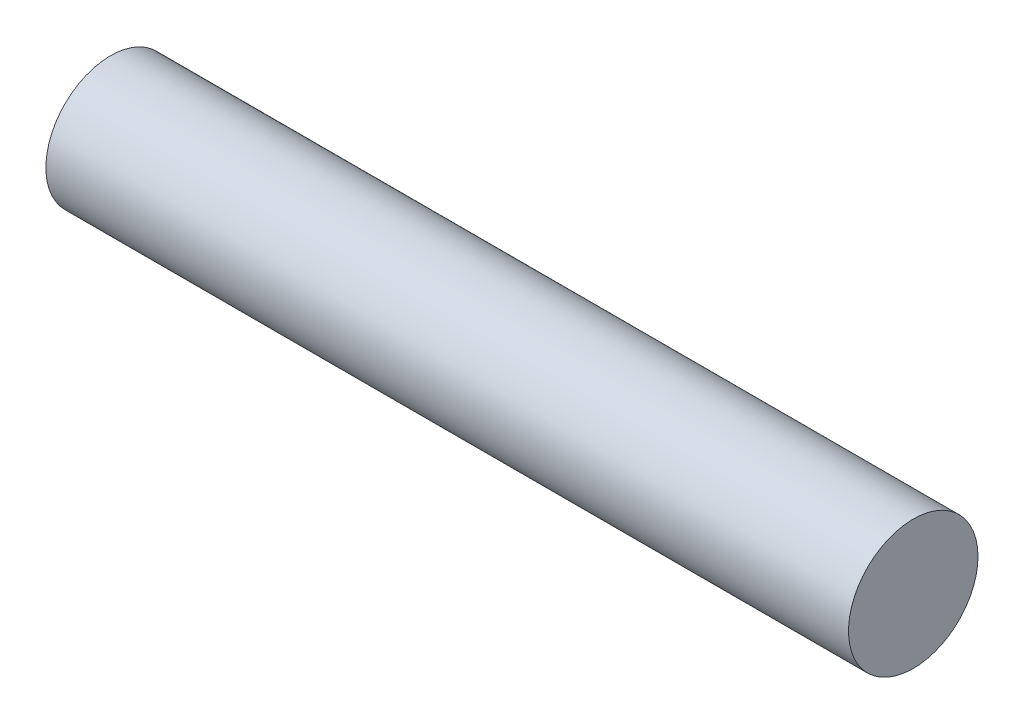
SolidWorks part; units mm, degrees
ref_plane "Front Plane" through (0, 0, 0) normal (0, 0, 1) x (1, 0, 0)
ref_plane "Top Plane" through (0, 0, 0) normal (0, 1, 0) x (1, 0, 0)
ref_plane "Right Plane" through (0, 0, 0) normal (1, 0, 0) x (0, 0, -1)
sketch "Sketch1" plane through (0, 0, 0) normal (1, 0, 0) x (0, 0, -1)
  circle A0 centre (0, 0) radius 2.5
  dimension "D1" = 5
extrude "Boss-Extrude1" add sketch "Sketch1" along normal mid plane 31
